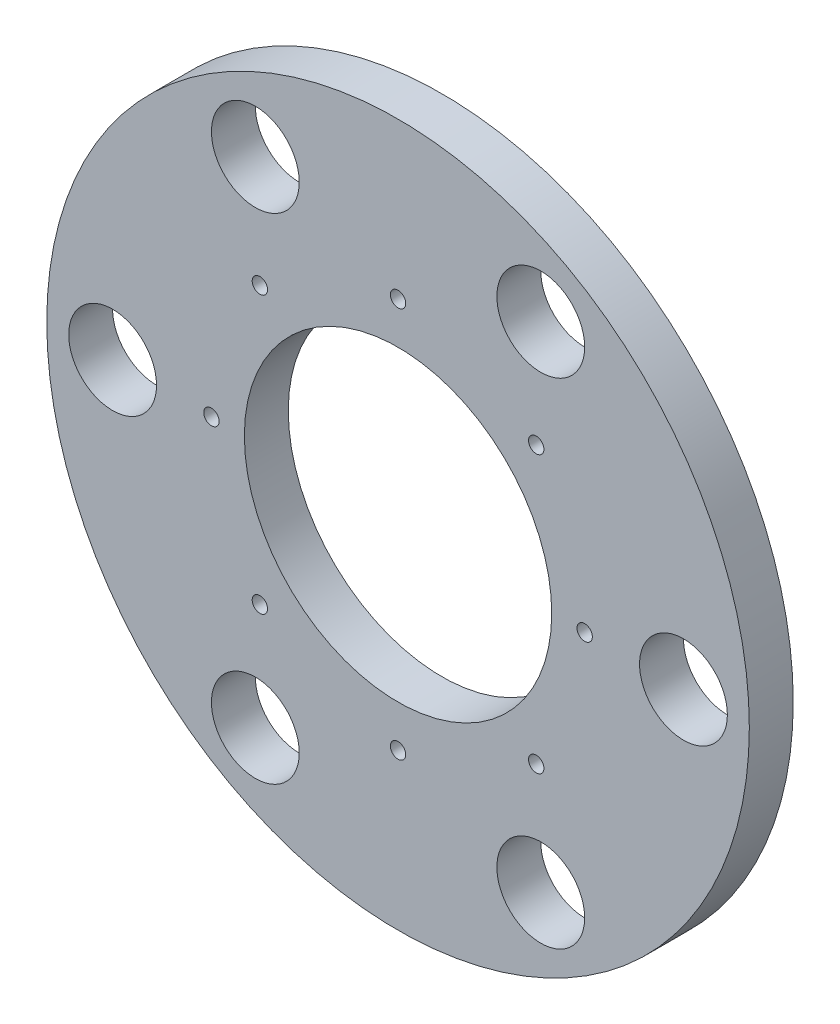
SolidWorks part; units mm, degrees
ref_plane "前视基准面" through (0, 0, 0) normal (0, 0, 1) x (1, 0, 0)
ref_plane "上视基准面" through (0, 0, 0) normal (0, 1, 0) x (1, 0, 0)
ref_plane "右视基准面" through (0, 0, 0) normal (1, 0, 0) x (0, 0, -1)
sketch "草图1" plane through (0, 0, 0) normal (0, 0, 1) x (1, 0, 0)
  line L2 (93.8169, 0) -> (107.4459, -5.5686)
  line L3 (107.4459, -5.5686) -> (107.6524, -5.9816)
  circle A0 centre (0, 0) radius 80
  circle A1 centre (0, 0) radius 29.5 construction
  circle A2 centre (0, 0) radius 44.5 construction
  circle A3 centre (-42.5, 0) radius 1.75
  circle A6 centre (42.5, 0) radius 1.75
  circle A9 centre (-21.25, 36.8061) radius 1.75
  circle A10 centre (21.25, 36.8061) radius 1.75
  circle A11 centre (-21.25, -36.8061) radius 1.75
  circle A12 centre (21.25, -36.8061) radius 1.75
  circle A14 centre (-22.25, 38.5381) radius 1.75
  circle A15 centre (22.25, 38.5381) radius 1.75
  circle A17 centre (22.25, -38.5381) radius 1.75
  circle A18 centre (-22.25, -38.5381) radius 1.75
  circle A19 centre (0, 0) radius 29.5
  point P25 (0, 0)
  point P38 (0, 0)
  dimension "D1" = 160
  dimension "D2" = 89
  dimension "D3" = 59
  dimension "D4" = 3.5
  dimension "D6" = 6
sketch "草图2" plane through (0, 0, 0) normal (0, 0, 1) x (1, 0, 0)
  circle A0 centre (0, 0) radius 48.25
  dimension "D1" = 96.5
sketch "草图3" plane through (0, 0, 0) normal (0, 0, 1) x (1, 0, 0)
  circle A0 centre (0, 0) radius 80
extrude "凸台-拉伸1" add sketch "草图3" against normal blind 10
sketch "草图4" plane through (0, 0, 0) normal (0, 0, 1) x (1, 0, 0)
  circle A0 centre (0, 0) radius 35
  dimension "D1" = 70
extrude "切除-拉伸1" cut sketch "草图4" against normal blind 7
sketch "草图5" plane through (0, 0, 0) normal (0, 0, 1) x (1, 0, 0)
  line L0 (0, 0) -> (-48.25, 0)
  circle A4 centre (-42.5, 0) radius 1.75
  circle A11 centre (0, 0) radius 48.25 construction
  circle A14 centre (-31.4663, 31.4663) radius 1.75
  circle A15 centre (0, 44.5) radius 1.75
  circle A16 centre (31.4663, 31.4663) radius 1.75
  circle A18 centre (31.4663, -31.4663) radius 1.75
  circle A19 centre (0, -44.5) radius 1.75
  circle A20 centre (-31.4663, -31.4663) radius 1.75
  circle A21 centre (42.5, 0) radius 1.75
  point P41 (0, 0)
sketch "草图6" plane through (0, 0, 0) normal (0, 0, 1) x (1, 0, 0)
  line L0 (0, 0) -> (-80, 0)
  circle A0 centre (0, 0) radius 80 construction
  circle A1 centre (-65, 0) radius 10
  circle A2 centre (-32.5, 56.2917) radius 10
  circle A3 centre (32.5, 56.2917) radius 10
  circle A4 centre (65, 0) radius 10
  circle A5 centre (32.5, -56.2917) radius 10
  circle A6 centre (-32.5, -56.2917) radius 10
  point P20 (0, 0)
  dimension "D1" = 20
  dimension "D2" = 15
  dimension "D3" = 6
extrude "切除-拉伸3" cut sketch "草图6" against normal blind 10 contours A2 | L0 A1 | L0 A1 | A6 | A5 | A4 | A3
extrude "切除-拉伸4" cut sketch "草图5" against normal blind 10 contours A15 | A16 | A21 | A18 | A20 | L0 A4 | L0 A4 | A14 | A19
sketch "草图7" plane through (0, 0, 0) normal (0, 0, 1) x (1, 0, 0)
  circle A0 centre (0, 0) radius 35
extrude "切除-拉伸5" cut sketch "草图7" against normal mid plane 40
